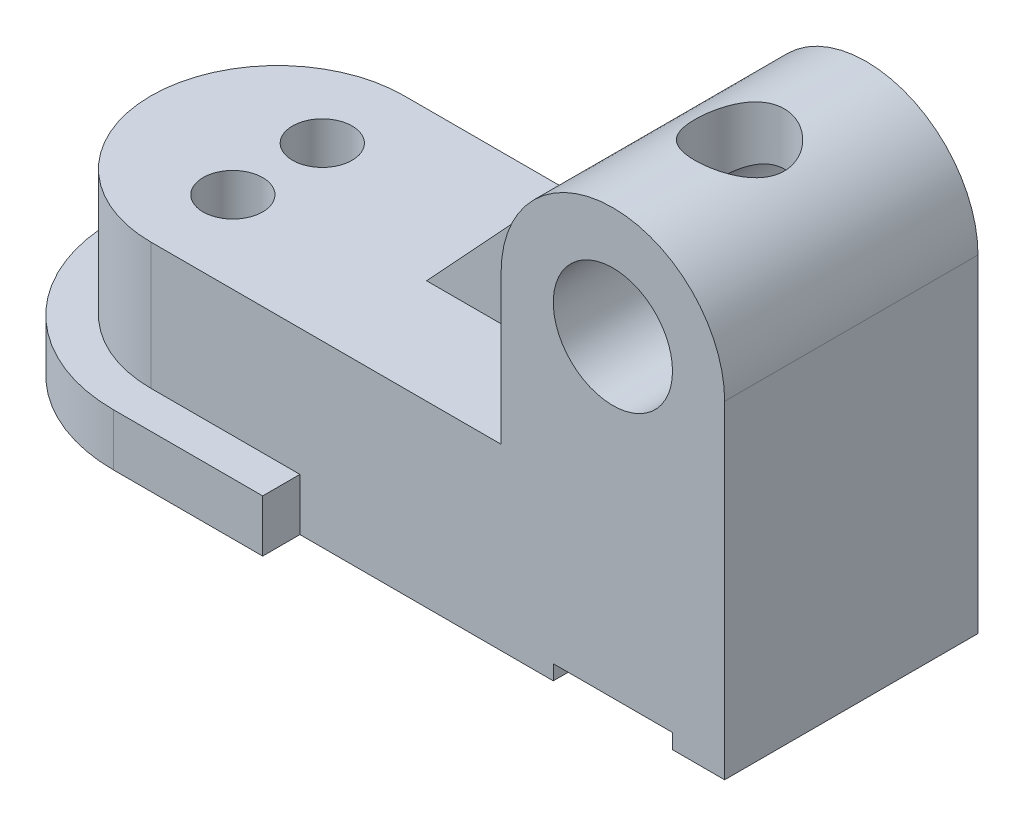
SolidWorks part; units mm, degrees
ref_plane "前视基准面" through (0, 0, 0) normal (0, 0, 1) x (1, 0, 0)
ref_plane "上视基准面" through (0, 0, 0) normal (0, 1, 0) x (1, 0, 0)
ref_plane "右视基准面" through (0, 0, 0) normal (1, 0, 0) x (0, 0, -1)
other "Configuration Table"
sketch "草图1" plane through (0, 0, 0) normal (0, 1, 0) x (1, 0, 0)
  line L1 (10, -22) -> (-10, -22)
  line L2 (10, -22) -> (10, 22)
  line L3 (10, 22) -> (-10, 22)
  line L5 (10, -22) -> (-10, 22) construction
  line L6 (10, 22) -> (-10, -22) construction
  arc A0 (-10, 22) -> (-10, -22) centre (-10, 0) ccw
  point P0 (0, 0)
  dimension "D1" = 20
  dimension "D2" = 44
extrude "凸台-拉伸1" add sketch "草图1" along normal blind 7
sketch "草图3" plane through (0, 7, 0) normal (0, 1, 0) x (1, 0, 0)
  line L1 (-10, 17) -> (67, 17)
  line L3 (-10, -17) -> (67, -17)
  line L4 (67, 17) -> (67, -17)
  arc A0 (-10, 17) -> (-10, -17) centre (-10, 0) ccw
  dimension "D1" = 77
  dimension "D3" = 17
  dimension "D2" = 34
  dimension "D4" = 67
extrude "凸台-拉伸2" add sketch "草图3" along normal blind 17 and the other way blind 7
sketch "草图4" plane through (0, 0, 0) normal (0, -1, 0) x (1, 0, 0)
  line L1 (-10, 12) -> (26, 12)
  line L3 (-10, -12) -> (26, -12)
  line L4 (26, 12) -> (26, -12)
  arc A0 (-10, 12) -> (-10, -12) centre (-10, 0) ccw
  dimension "D1" = 36
  dimension "D3" = 12
  dimension "D2" = 24
  dimension "D4" = 26
extrude "切除-拉伸1" cut sketch "草图4" against normal blind 16
sketch "草图5" plane through (0, 24, 0) normal (0, 1, 0) x (1, 0, 0)
  circle A0 centre (-10, 6) radius 4
  circle A1 centre (-10, -6) radius 4
  dimension "D1" = 6
  dimension "D3" = 8
  dimension "D4" = 8
  dimension "D2" = 6
  dimension "D5" = 10
  dimension "D6" = 10
extrude "切除-拉伸2" cut sketch "草图5" against normal up to next
sketch "草图6" plane through (0, 24, 0) normal (0, 1, 0) x (1, 0, 0)
  line L0 (-10, -17) -> (67, -17) construction
  line L1 (67, 17) -> (37, 17)
  line L2 (67, 17) -> (67, -17)
  line L3 (67, -17) -> (37, -17)
  line L4 (37, 17) -> (37, -17)
  dimension "D1" = 30
extrude "凸台-拉伸3" add sketch "草图6" along normal blind 20
sketch "草图7" plane through (0, 0, 17) normal (0, 0, 1) x (1, 0, 0)
  line L2 (37, 44) -> (67, 44) construction
  line L3 (37, 44) -> (67, 44)
  arc A0 (37, 44) -> (67, 44) centre (52, 44) cw
  line M4 (67, 44) -> (37, 44)
extrude "凸台-拉伸4" add sketch "草图7" against normal blind 34 contours A0 M4
sketch "草图8" plane through (0, 0, 17) normal (0, 0, 1) x (1, 0, 0)
  circle A0 centre (52, 44) radius 8
extrude "切除-拉伸3" cut sketch "草图8" against normal up to next
sketch "草图9" plane through (0, 0, 0) normal (0, 0, 1) x (1, 0, 0)
  line L0 (13, 24) -> (41.0006, 54.1987)
  line L1 (-10, 24) -> (37, 24) construction
  arc A0 (67, 44) -> (37, 44) centre (52, 44) ccw construction
  dimension "D1" = 24
rib "筋1" sketch "草图9" sketch "草图9" thickness 6 extrusion direction parallel to sketch draft on no parameters "D1"=6
ref_plane "基准面1" through (0, 59, 0) normal (0, 1, 0) x (1, 0, 0)
sketch "草图10" plane through (0, 59, 0) normal (0, 1, 0) x (1, 0, 0)
  line L0 (67, -17) -> (67, 17) construction
  circle A0 centre (52, 0) radius 6
  dimension "D1" = 15
  dimension "D2" = 12
extrude "切除-拉伸4" cut sketch "草图10" against normal through all
sketch "草图11" plane through (0, 0, 17) normal (0, 0, 1) x (1, 0, 0)
  line L0 (10, 0) -> (67, 0) construction
  line L1 (60, -2) -> (44, -2)
  line L2 (60, -2) -> (60, 2)
  line L3 (60, 2) -> (44, 2)
  line L4 (44, -2) -> (44, 2)
  line L5 (60, -2) -> (44, 2) construction
  line L6 (60, 2) -> (44, -2) construction
  line L7 (67, 0) -> (67, 44) construction
  point P0 (52, 0)
  dimension "D1" = 15
  dimension "D2" = 16
  dimension "D3" = 4
extrude "切除-拉伸5" cut sketch "草图11" against normal through all
sketch "草图12" plane through (0, 0, 0) normal (0, -1, 0) x (1, 0, 0)
  line L0 (26, -12) -> (26, 12) construction
  line L1 (1.6046, -5) -> (50.3954, -5)
  line L2 (1.6046, -5) -> (1.6046, 5)
  line L3 (1.6046, 5) -> (50.3954, 5)
  line L4 (50.3954, -5) -> (50.3954, 5)
  line L5 (1.6046, -5) -> (50.3954, 5) construction
  line L6 (1.6046, 5) -> (50.3954, -5) construction
  point P0 (26, 0)
  dimension "D1" = 10
extrude "切除-拉伸8" cut sketch "草图12" against normal blind 16 contours L3 L4 L1 L2
